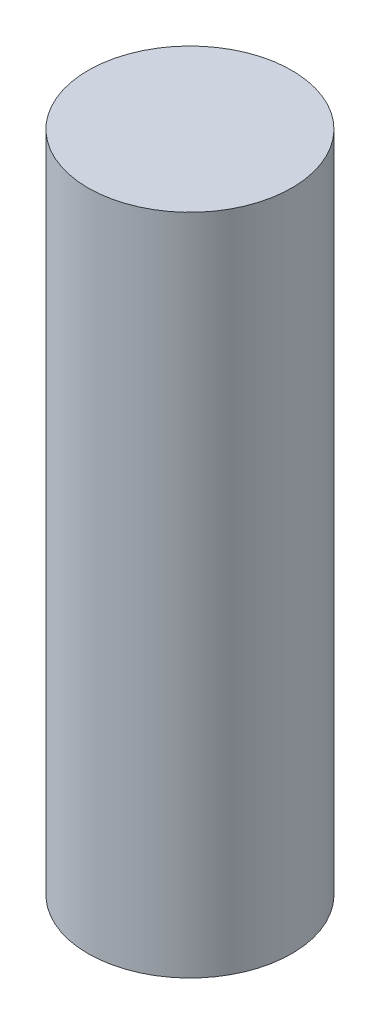
SolidWorks part; units mm, degrees
material "Cast Alloy Steel"
ref_plane "Front Plane" through (0, 0, 0) normal (0, 0, 1) x (1, 0, 0)
ref_plane "Top Plane" through (0, 0, 0) normal (0, 1, 0) x (1, 0, 0)
ref_plane "Right Plane" through (0, 0, 0) normal (1, 0, 0) x (0, 0, -1)
sketch "Sketch1" plane through (0, 0, 0) normal (0, 1, 0) x (1, 0, 0)
  circle A0 centre (0, 0) radius 10.775
  dimension "D1" = 21.55
extrude "Boss-Extrude1" add sketch "Sketch1" along normal blind 70.15
